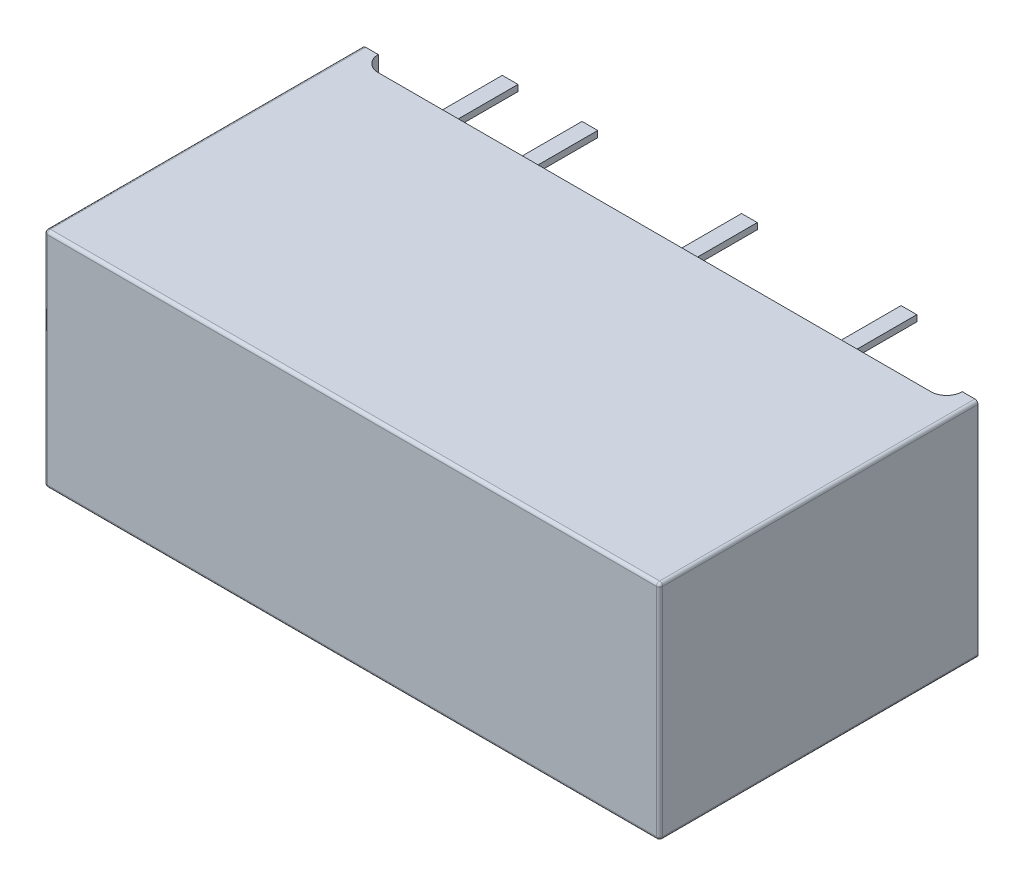
SolidWorks part; units mm, degrees
ref_plane "Front" through (0, 0, 0) normal (0, 0, 1) x (1, 0, 0)
ref_plane "Top" through (0, 0, 0) normal (0, 1, 0) x (1, 0, 0)
ref_plane "Right" through (0, 0, 0) normal (1, 0, 0) x (0, 0, -1)
sketch "Эскиз1" plane through (0, 0, 0) normal (0, 1, 0) x (1, 0, 0)
  line L0 (-9.8, 0) -> (-9.3, 0)
  line L1 (-9.8, 0) -> (-9.8, -10.14)
  line L2 (-9.8, -10.14) -> (9.8, -10.14)
  line L3 (9.8, -10.14) -> (9.8, 0)
  line L4 (9.8, 0) -> (9.3, 0)
  line L5 (8.8, -0.5) -> (-8.8, -0.5)
  line L6 (0, 0) -> (0, -10.14) construction
  arc A0 (9.3, 0) -> (8.8, -0.5) centre (8.8, 0) cw
  arc A1 (-8.8, -0.5) -> (-9.3, 0) centre (-8.8, 0) cw
  point P14 (0, -0.5)
  dimension "D1" = 0.5
  dimension "D2" = 19.6
  dimension "D3" = 10.14
  dimension "D4" = 0.5
extrude "Бобышка-Вытянуть1" add sketch "Эскиз1" along normal mid plane 7.1
sketch "Эскиз2" plane through (0, -3.55, 0) normal (0, -1, 0) x (1, 0, 0)
  text T0 "<b><i>SPR01x-xx</i></b>" font "Century Gothic" height 2.55
extrude "Бобышка-Вытянуть2" add sketch "Эскиз2" along normal blind 0.01
fillet "Скругление1" radius 0.1 8 edges at (-9.8, 0, 10.14) (0, 3.55, 10.14) (9.8, 0, 10.14) (0, -3.55, 10.14) (-9.8, 3.55, 5.07) (9.8, 3.55, 5.07) (9.8, -3.55, 5.07) (-9.8, -3.55, 5.07)
sketch "Эскиз3" plane through (0, 0, 0.5) normal (0, 0, -1) x (-1, 0, 0)
  line L0 (7.6, 2.35) -> (5.06, 2.35) construction
  line L1 (7.85, 2.45) -> (7.35, 2.45)
  line L2 (7.85, 2.45) -> (7.85, 2.25)
  line L3 (7.85, 2.25) -> (7.35, 2.25)
  line L4 (7.35, 2.45) -> (7.35, 2.25)
  line L5 (7.85, 2.45) -> (7.35, 2.25) construction
  line L6 (7.85, 2.25) -> (7.35, 2.45) construction
  line L7 (5.31, 2.45) -> (4.81, 2.45)
  line L8 (5.31, 2.45) -> (5.31, 2.25)
  line L9 (5.31, 2.25) -> (4.81, 2.25)
  line L10 (4.81, 2.45) -> (4.81, 2.25)
  line L11 (5.31, 2.45) -> (4.81, 2.25) construction
  line L12 (5.31, 2.25) -> (4.81, 2.45) construction
  line L13 (0.23, 2.45) -> (-0.27, 2.45)
  line L14 (0.23, 2.45) -> (0.23, 2.25)
  line L15 (0.23, 2.25) -> (-0.27, 2.25)
  line L16 (-0.27, 2.45) -> (-0.27, 2.25)
  line L17 (0.23, 2.45) -> (-0.27, 2.25) construction
  line L18 (0.23, 2.25) -> (-0.27, 2.45) construction
  line L19 (-4.85, 2.45) -> (-5.35, 2.45)
  line L20 (-4.85, 2.45) -> (-4.85, 2.25)
  line L21 (-4.85, 2.25) -> (-5.35, 2.25)
  line L22 (-5.35, 2.45) -> (-5.35, 2.25)
  line L23 (-4.85, 2.45) -> (-5.35, 2.25) construction
  line L24 (-4.85, 2.25) -> (-5.35, 2.45) construction
  line L25 (5.06, 2.35) -> (-0.02, 2.35) construction
  line L26 (-0.02, 2.35) -> (-5.1, 2.35) construction
  line L27 (7.6, 2.35) -> (9.8, 2.35) construction
  line L28 (9.8, 3.45) -> (9.8, -3.45) construction
  line L29 (-8.8, 3.55) -> (8.8, 3.55) construction
  point P0 (7.6, 2.35)
  point P5 (5.06, 2.35)
  point P10 (-0.02, 2.35)
  point P15 (-5.1, 2.35)
  dimension "D1" = 0.5
  dimension "D2" = 2.2
  dimension "D3" = 2.54
  dimension "D4" = 5.08
  dimension "D5" = 5.08
  dimension "D6" = 1.2
  dimension "D7" = 0.2
extrude "Бобышка-Вытянуть4" add sketch "Эскиз3" along direction (0, 0, 1) on the side of the normal offset from surface (3 mm away) 2.5
